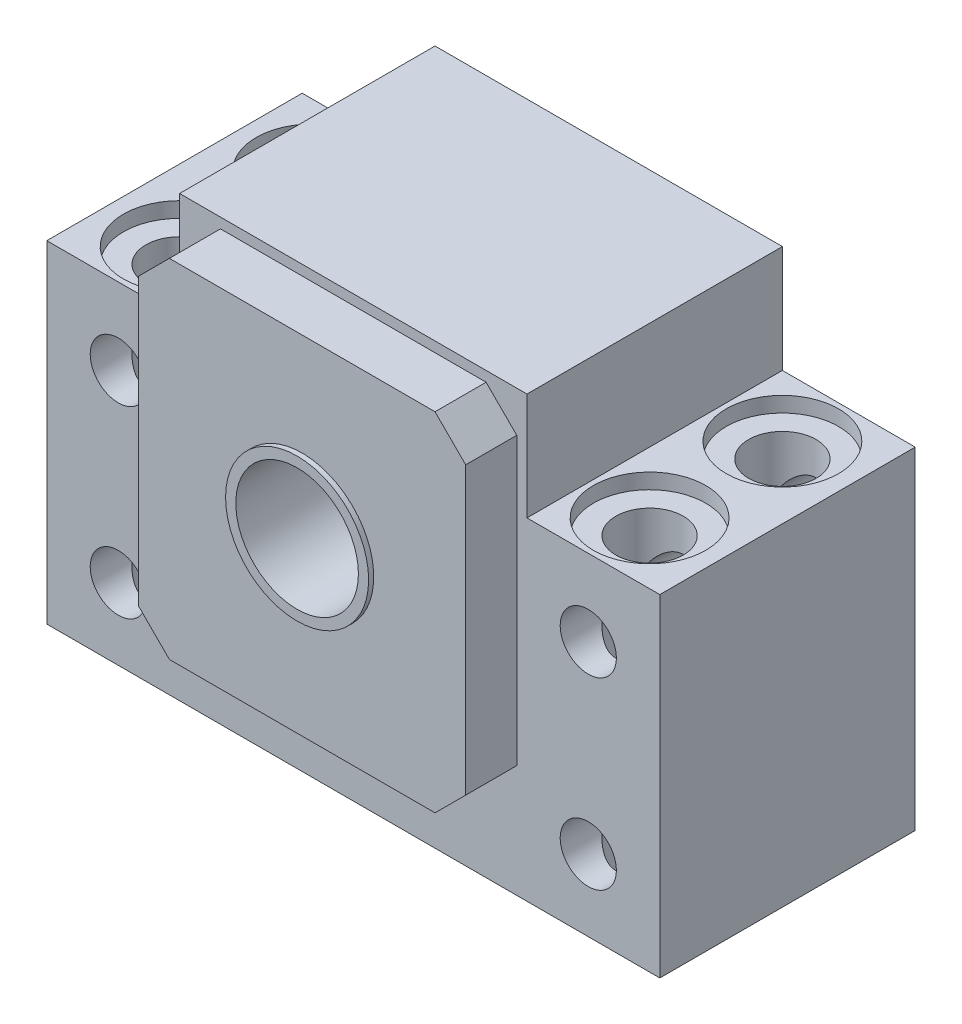
SolidWorks part; units mm, degrees
ref_plane "Alzado" through (0, 0, 0) normal (0, 0, 1) x (1, 0, 0)
ref_plane "Planta" through (0, 0, 0) normal (0, 1, 0) x (1, 0, 0)
ref_plane "Vista lateral" through (0, 0, 0) normal (1, 0, 0) x (0, 0, -1)
sketch "Croquis1" plane through (0, 0, 0) normal (0, 0, 1) x (1, 0, 0)
  line L0 (0, 0) -> (60, 0)
  line L1 (60, 0) -> (60, 32.5)
  line L2 (60, 32.5) -> (47, 32.5)
  line L3 (47, 32.5) -> (47, 43)
  line L4 (47, 43) -> (13, 43)
  line L5 (13, 43) -> (13, 32.5)
  line L6 (13, 32.5) -> (0, 32.5)
  line L7 (0, 32.5) -> (0, 0)
  line L8 (30, 43) -> (30, 0.9008) construction
  line L10 (7, 7) -> (53, 7) construction
  line L11 (7, 7) -> (7, 25) construction
  line L12 (7, 25) -> (53, 25) construction
  line L13 (53, 7) -> (53, 25) construction
  line L14 (7, 7) -> (53, 25) construction
  line L15 (7, 25) -> (53, 7) construction
  circle A0 centre (30, 25) radius 13 construction
  circle A1 centre (7, 25) radius 2.75
  circle A2 centre (53, 25) radius 2.75
  circle A3 centre (53, 7) radius 2.75
  circle A4 centre (7, 7) radius 2.75
  point P13 (30, 16)
  dimension "D6" = 26
  dimension "D7" = 25
  dimension "D10" = 0
  dimension "D11" = 5.5
  dimension "D1" = 43
  dimension "D2" = 32.5
  dimension "D3" = 60
  dimension "D4" = 34
  dimension "D5" = 13
  dimension "D8" = 46
  dimension "D9" = 18
extrude "Saliente-Extruir1" add sketch "Croquis1" along normal blind 25
sketch "Croquis2" plane through (0, 0, 25) normal (0, 0, 1) x (1, 0, 0)
  circle A0 centre (30, 25) radius 6
  dimension "D1" = 12
extrude "Cortar-Extruir1" cut sketch "Croquis2" against normal up to surface (25 mm away) up to face at (55.75, 7, 0)
sketch "Croquis3" plane through (0, 0, 25) normal (0, 0, 1) x (1, 0, 0)
  circle A0 centre (30, 25) radius 13
  dimension "D1" = 26
sketch "Croquis4" plane through (0, 0, 0) normal (0, 0, -1) x (-1, 0, 0)
  circle A0 centre (-30, 25) radius 13
  dimension "D1" = 26
sketch "Croquis5" plane through (0, 32.5, 0) normal (0, 1, 0) x (1, 0, 0)
  line L0 (0, -6) -> (60, -6) construction
  line L1 (0, -12.5) -> (60, -12.5) construction
  line L2 (13, 0) -> (0, 0) construction
  line L3 (0, -25) -> (0, 0) construction
  line L4 (60, -25) -> (60, 0) construction
  line L5 (17, -25) -> (43, -25) construction
  line L7 (7, -6) -> (7, -25) construction
  line L8 (13, -25) -> (0, -25) construction
  line L9 (53, -6) -> (53, -25) construction
  line L10 (60, -25) -> (47, -25) construction
  line L11 (7, -19) -> (53, -19) construction
  circle A0 centre (7, -6) radius 3.3
  circle A1 centre (53, -6) radius 3.3
  circle A2 centre (7, -19) radius 3.3
  circle A3 centre (53, -19) radius 3.3
  dimension "D1" = 6.6
  dimension "D2" = 7
  dimension "D3" = 7
  dimension "D6" = 6
  dimension "D8" = 46
  dimension "D4" = 13
  dimension "D5" = 6
extrude "Cortar-Extruir4" cut sketch "Croquis5" against normal through all
sketch "Croquis6" plane through (0, 32.5, 0) normal (0, 1, 0) x (1, 0, 0)
  line L0 (7, -6) -> (7, -19) construction
  line L1 (7, -19) -> (53, -19) construction
  line L2 (53, -19) -> (53, -6) construction
  line L3 (53, -6) -> (7, -6) construction
  line L4 (13, 0) -> (0, 0) construction
  circle A0 centre (7, -6) radius 5.5
  circle A1 centre (53, -6) radius 5.5
  circle A2 centre (7, -19) radius 5.5
  circle A3 centre (53, -19) radius 5.5
  dimension "D1" = 11
  dimension "D2" = 6
  dimension "D3" = 46
extrude "Cortar-Extruir5" cut sketch "Croquis6" against normal blind 1.5
sketch "Croquis7" plane through (0, 0, 25) normal (0, 0, 1) x (1, 0, 0)
  line L1 (14, 8) -> (46, 8)
  line L2 (14, 8) -> (14, 42)
  line L3 (14, 42) -> (46, 42)
  line L4 (46, 8) -> (46, 42)
  line L5 (14, 8) -> (46, 42) construction
  line L6 (14, 42) -> (46, 8) construction
  circle A0 centre (30, 25) radius 6
  point P0 (30, 25)
  dimension "D3" = 12
  dimension "D1" = 34
  dimension "D2" = 32
extrude "Saliente-Extruir2" add sketch "Croquis7" along normal blind 5
sketch "Croquis8" plane through (0, 0, 30) normal (0, 0, 1) x (1, 0, 0)
  circle A0 centre (30, 25) radius 6
  circle A1 centre (30, 25) radius 7
  dimension "D1" = 12
  dimension "D2" = 14
extrude "Saliente-Extruir3" add sketch "Croquis8" along normal blind 0.5
sketch "Croquis9" plane through (0, 0, 0) normal (0, 0, -1) x (-1, 0, 0)
  circle A0 centre (-30, 25) radius 6
  circle A1 centre (-30, 25) radius 7
  dimension "D1" = 12
  dimension "D2" = 14
extrude "Saliente-Extruir4" add sketch "Croquis9" along normal blind 0.5
chamfer "Chaflán1" distance 3 angle 45 4 edges at (46, 8, 27.5) (14, 8, 27.5) (46, 42, 27.5) (14, 42, 27.5)
